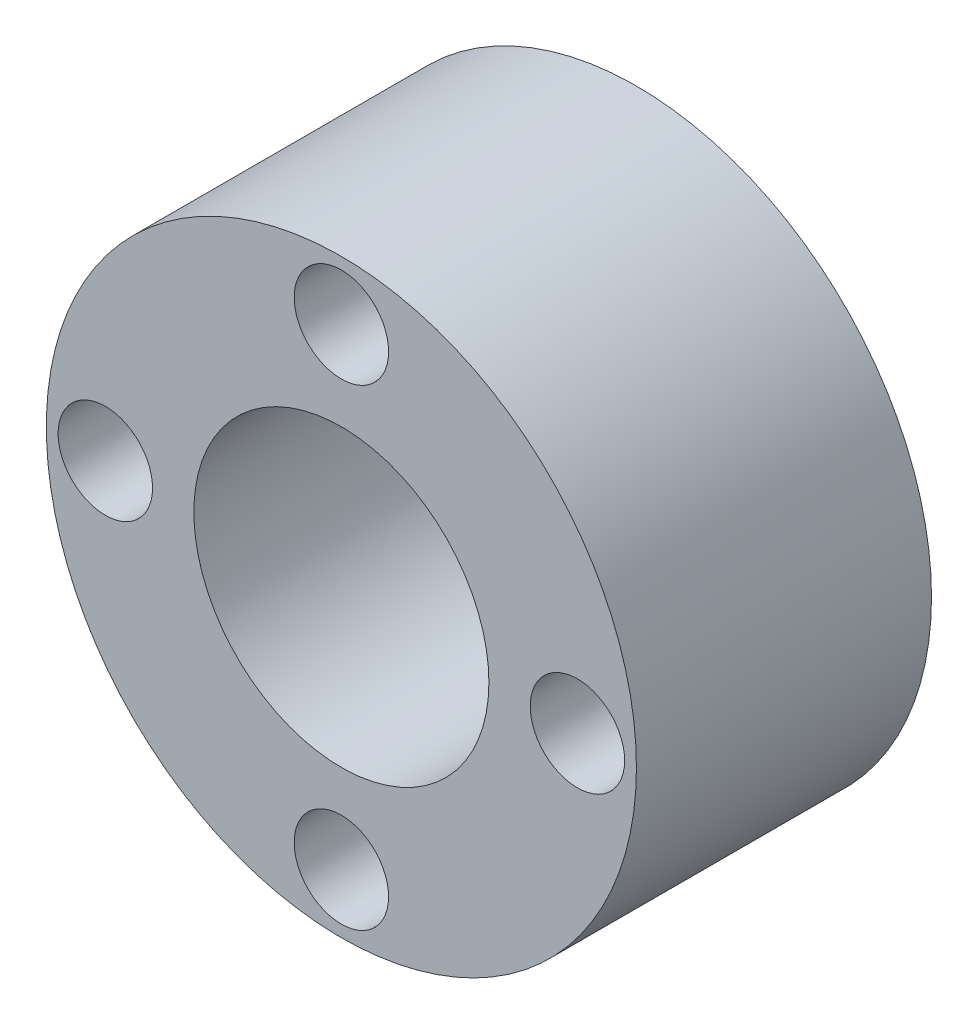
SolidWorks part; units mm, degrees
ref_plane "前视基准面" through (0, 0, 0) normal (0, 0, 1) x (1, 0, 0)
ref_plane "上视基准面" through (0, 0, 0) normal (0, 1, 0) x (1, 0, 0)
ref_plane "右视基准面" through (0, 0, 0) normal (1, 0, 0) x (0, 0, -1)
other "Configuration Table"
sketch "草图1" plane through (0, 0, 0) normal (0, 0, 1) x (1, 0, 0)
  circle A0 centre (0, 0) radius 4 construction
  circle A1 centre (0, 0) radius 5
  circle A2 centre (0, 0) radius 2.5
  circle A3 centre (0, 4) radius 0.8
  circle A4 centre (4, 0) radius 0.8
  circle A5 centre (0, -4) radius 0.8
  circle A6 centre (-4, 0) radius 0.8
  point P16 (0, 0)
  dimension "D1" = 8
  dimension "D2" = 10
  dimension "D3" = 5
  dimension "D4" = 1.6
  dimension "D5" = 4
extrude "凸台-拉伸1" add sketch "草图1" along normal blind 5
